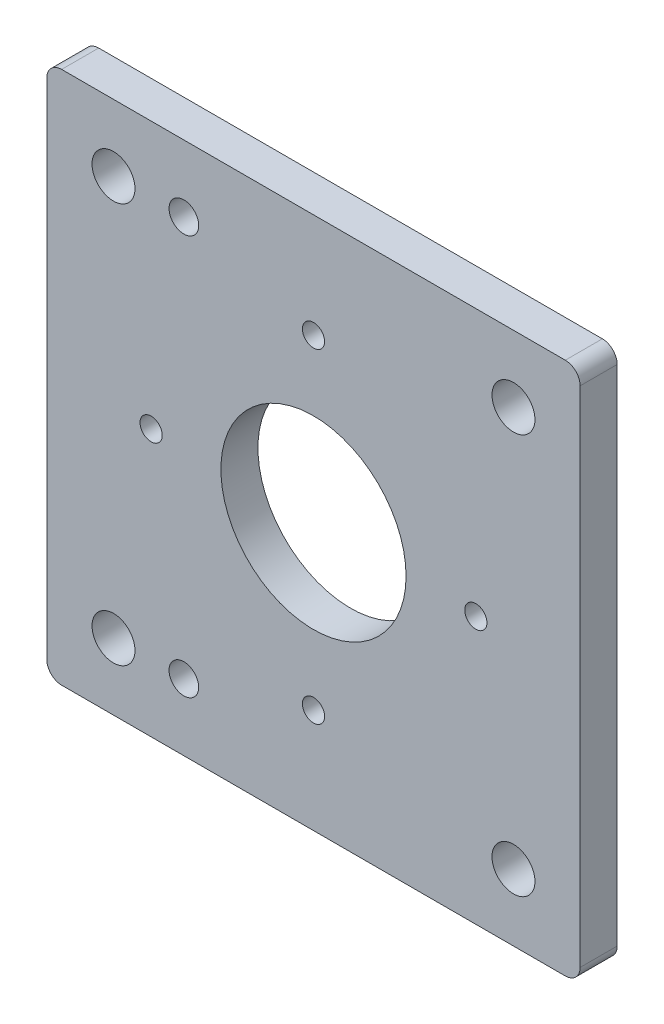
SolidWorks part; units mm, degrees
ref_plane "Front" through (0, 0, 0) normal (0, 0, 1) x (1, 0, 0)
ref_plane "Top" through (0, 0, 0) normal (0, 1, 0) x (1, 0, 0)
ref_plane "Right" through (0, 0, 0) normal (1, 0, 0) x (0, 0, -1)
sketch "Sketch1" plane through (0, 0, 0) normal (0, 0, 1) x (1, 0, 0)
  line L1 (36, -36) -> (-36, -36)
  line L2 (36, -36) -> (36, 36)
  line L3 (36, 36) -> (-36, 36)
  line L4 (-36, -36) -> (-36, 36)
  line L5 (36, -36) -> (-36, 36) construction
  line L6 (36, 36) -> (-36, -36) construction
  circle A0 centre (-27, 27) radius 2.9
  circle A1 centre (27, 27) radius 2.9
  circle A2 centre (27, -27) radius 2.9
  circle A3 centre (-27, -27) radius 2.9
  circle A4 centre (0, 0) radius 12.5
  circle A5 centre (0, 21.92) radius 1.5
  circle A6 centre (0, -21.92) radius 1.5
  circle A7 centre (-21.92, 0) radius 1.5
  circle A8 centre (21.92, 0) radius 1.5
  circle A9 centre (-17.5, 27) radius 2
  circle A10 centre (-17.5, -27) radius 2
  point P0 (0, 0)
  dimension "D3" = 5.8
  dimension "D4" = 4
  dimension "D8" = 25
  dimension "D9" = 43.84
  dimension "D10" = 3
  dimension "D2" = 72
  dimension "D7" = 9
  dimension "D14" = 43.84
  dimension "D15" = 21.92
  dimension "D16" = 21.92
  dimension "D19" = 18.5
extrude "Boss-Extrude1" add sketch "Sketch1" along normal blind 5
fillet "Fillet1" radius 2 4 edges at (-36, -36, 2.5) (36, -36, 2.5) (-36, 36, 2.5) (36, 36, 2.5)
